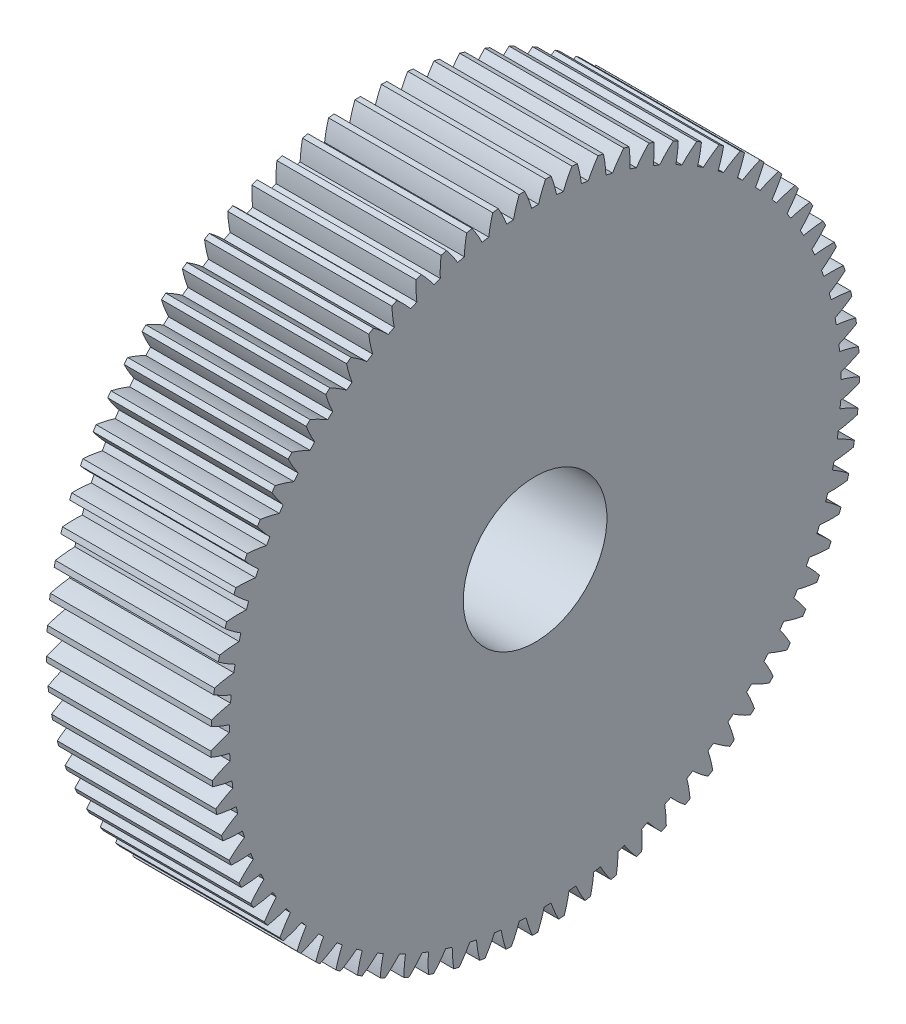
SolidWorks part; units mm, degrees
ref_plane "Plane1" through (0, 0, 0) normal (0, 0, 1) x (1, 0, 0)
ref_plane "Plane2" through (0, 0, 0) normal (0, 1, 0) x (1, 0, 0)
ref_plane "Plane3" through (0, 0, 0) normal (1, 0, 0) x (0, 0, -1)
other "Configuration Table"
sketch "HoldingSke" plane through (0, 0, 0) normal (0, 1, 0) x (1, 0, 0)
  line L0 (0, 0) -> (0.1125, -0.4872)
  line L1 (-15, 0) -> (100, 0) construction
  line L2 (0, 0) -> (-2.1039, 2.3779)
  line L3 (0, 0) -> (-11.863, 4.5341)
  line L4 (0, 0) -> (1.9427, 8.4147)
  line L5 (0, 0) -> (-46.8476, -17.4728)
  line L6 (0, 0) -> (-33.1585, -22.3721)
  line L7 (-2.1039, 2.3779) -> (8.6586, 51.2059)
  line L8 (-76.2, 54.61) -> (-72.9, 54.61)
  line L9 (-71.009, 38.7566) -> (-53.1078, 45.2721)
  line L10 (-76.2, 71.12) -> (104.1128, 71.12)
  line L11 (0, 0) -> (-40, 0)
  line L12 (-76.2, 101.6) -> (-76.133, 101.6)
  line L13 (24.9733, 27.94) -> (52.9518, 28.4284)
  line L14 (24.9733, 27.94) -> (24.9743, 27.94)
  line L15 (24.9733, 27.94) -> (100.4006, 29.5858)
  line L16 (-63.627, -2) -> (-12.827, -2)
  circle A0 centre (0, 0) radius 17.5
  circle A1 centre (0, 0) radius 37.5
  circle A2 centre (0, 0) radius 37.5
  circle A3 centre (0, 0) radius 17.5
  dimension "MHD" = 75
  dimension "Hub_dia" = 75
  dimension "Bore" = 35
  dimension "MBD" = 35
  dimension "Num_teeth" = 77
  dimension "Pitch" = 0.5
  dimension "Overall_len" = 50
  dimension "Show_teeth" = 77
  dimension "Thickness" = 40
  dimension "OAL" = 50.0001
  dimension "T_dim" = 3.3
  dimension "Ap" = 20
  dimension "H" = 19.05
  dimension "Pitch_radius" = 180.3128
  dimension "Width" = 40
  dimension "Backlash" = 0.067
  dimension "Addendum_fac" = 1
  dimension "Dedendum_fac" = 1.25
  dimension "Clearance_fac" = 0.25
  dimension "Dedendum_add" = 0.001
  dimension "Module" = 2
sketch "BasProSke" plane through (0, 0, 0) normal (0, 1, 0) x (1, 0, 0)
  line L0 (-10, 0) -> (60, 0) construction
  line L1 (0, 0) -> (0, 79)
  line L2 (0, 0) -> (40, 0)
  line L3 (40, 0) -> (40, 79)
  line L4 (40, 79) -> (0, 79)
  dimension "Thickness" = 40
  dimension "Diameter" = 158
revolve "Base-Revolve" add sketch "BasProSke" angle 360 about L0
sketch "TooCutSke" plane through (0, 0, 0) normal (1, 0, 0) x (0, 0, -1)
  line L1 (0, 0) -> (0, 107) construction
  line L2 (0, 0) -> (-1.6879, 76.9815) construction
  line L3 (0, 0) -> (-6.2803, 153.8444) construction
  line L4 (-1.6879, 76.9815) -> (-3.1402, 76.9222) construction
  arc A0 (0.8284, 74.4944) -> (-0.8284, 74.4944) centre (0, 0) ccw
  arc A1 (2.5605, 78.9839) -> (-2.5605, 78.9839) centre (0, 0) ccw
  circle A2 centre (0, 0) radius 77 construction
  circle A3 centre (0, 0) radius 72.3563 construction
  arc A4 (-0.8284, 74.4944) -> (-2.5605, 78.9839) centre (-30.3423, 65.687) ccw
  arc A5 (2.5605, 78.9839) -> (0.8284, 74.4944) centre (30.3423, 65.687) ccw
  dimension "Root_dia" = 148.998
  dimension "Overcut_dia" = 158.0508
  dimension "Pitch_dia" = 154
  dimension "Base_dia" = 144.7127
  dimension "Flank_rad" = 30.8
  dimension "Half_ang" = 2.338
  dimension "Half_CT" = 1.4534
extrude "ToothCut" cut sketch "TooCutSke" along normal through all
fillet "Breaks" [suppressed] radius 0.04
fillet "RootFillets" [suppressed] radius 0.501
pattern_circular "TeethCuts" count 77 every 4.675 about axis through (-10, 0, 0) along (1, 0, 0) of "ToothCut", "RootFillets", "Breaks"
sketch "HubNeaOneSke" plane through (0, 0, 0) normal (-1, 0, 0) x (0, 0, 1)
  circle A0 centre (0, 0) radius 37.5
  dimension "Diameter" = 75
extrude "HubNearOne" [suppressed] add sketch "HubNeaOneSke" along normal blind 10.0001
sketch "HubNeaBotSke" plane through (0, 0, 0) normal (-1, 0, 0) x (0, 0, 1)
  circle A0 centre (0, 0) radius 37.5
  dimension "Diameter" = 75
extrude "HubNearBoth" [suppressed] add sketch "HubNeaBotSke" along normal blind 5
ref_plane "FarPln" through (40, 0, 0) normal (1, 0, 0) x (0, 0, -1)
sketch "HubFarSke" plane through (40, 0, 0) normal (1, 0, 0) x (0, 0, -1)
  circle A0 centre (0, 0) radius 37.5
  dimension "Diameter" = 75
extrude "HubFar" [suppressed] add sketch "HubFarSke" along normal blind 5
sketch "BorSke" plane through (0, 0, 0) normal (1, 0, 0) x (0, 0, -1)
  circle A0 centre (0, 0) radius 17.5
  dimension "Diameter" = 35
extrude "Bore" cut sketch "BorSke" along normal mid plane 100.0001
sketch "KeySke" plane through (0, 0, 0) normal (1, 0, 0) x (0, 0, -1)
  line L0 (-5, 0) -> (-5, 20.8)
  line L1 (-5, 20.8) -> (5, 20.8)
  line L2 (5, 20.8) -> (5, 0)
  line L3 (0, 0) -> (0, 34) construction
  line L4 (-5, 0) -> (5, 0)
  dimension "Offset" = 20.8
  dimension "Width" = 10
extrude "Keyway" [suppressed] cut sketch "KeySke" along normal mid plane 100.0001
pattern_circular "Keyway2" [suppressed] count 2 every 90 about axis through (-10, 0, 0) along (1, 0, 0)
equation "' \"Module@HoldingSke\" = 6.35"
equation "' \"Num_teeth@HoldingSke\" = 12"
equation "' \"Ap@HoldingSke\" =  20"
equation "' \"Ap@HoldingSke\" = 20"
equation "' \"Width@HoldingSke\" = 0.5 * 25.4"
equation "' \"Hub_dia@HoldingSke\"= 1 * 25.4"
equation "' \"Hub_dia@HoldingSke\" = 1 * 25.4"
equation "' \"Overall_len@HoldingSke\" = 1.0 * 25.4"
equation "' \"Bore@HoldingSke\" = 0.75 * 25.4"
equation "' \"T_dim@HoldingSke\" = 0.1 * 25.4"
equation "' \"Width@KeySke\" = 0.25 * 25.4"
equation "' \"Show_teeth@HoldingSke\" = 13"
equation "' \"Backlash@HoldingSke\" = 0.009 * 25.4"
equation "' \"Addendum_fac@HoldingSke\" = 1.0"
equation "' \"Dedendum_fac@HoldingSke\" = 1.25"
equation "' \"Dedendum_add@HoldingSke\" = 0.00005 * 25.4"
equation "' \"Clearance_fac@HoldingSke\" = 0.25"
equation "\"Pitch@HoldingSke\" = 1 / \"Module@HoldingSke\""
equation "\"Overcut_dia@TooCutSke\" = (\"Num_teeth@HoldingSke\" + 2 * \"Addendum_fac@HoldingSke\") / \"Pitch@HoldingSke\" + 0.002 * 25.4"
equation "\"Pitch_dia@TooCutSke\" = \"Num_teeth@HoldingSke\" / \"Pitch@HoldingSke\""
equation "\"Base_dia@TooCutSke\" = \"Num_teeth@HoldingSke\" / \"Pitch@HoldingSke\" * cos((\"Ap@HoldingSke\"  * 3.14159265 / 180))"
equation "\"Root_dia@TooCutSke\" = (\"Num_teeth@HoldingSke\" + 2) / \"Pitch@HoldingSke\" - 2 * (\"Addendum_fac@HoldingSke\" + \"Dedendum_fac@HoldingSke\") / \"Pitch@HoldingSke\" - \"Dedendum_add@HoldingSke\" * 2"
equation "\"Half_ang@TooCutSke\" = 180 / \"Num_teeth@HoldingSke\""
equation "\"Half_CT@TooCutSke\" = \"Num_teeth@HoldingSke\" / \"Pitch@HoldingSke\" * sin((3.14159265 / 2 / \"Num_teeth@HoldingSke\")) / 2 - 7 * \"Backlash@HoldingSke\" / 4"
equation "\"Flank_rad@TooCutSke\" = \"Num_teeth@HoldingSke\" / \"Pitch@HoldingSke\" / 5"
equation "\"Radius@RootFillets\" = \"Clearance_fac@HoldingSke\" / \"Pitch@HoldingSke\" + \"Dedendum_add@HoldingSke\""
equation "\"Break_rad@Breaks\" = 0.02 / \"Pitch@HoldingSke\""
equation "\"Thickness@HoldingSke\" = \"Width@HoldingSke\""
equation "\"OAL@HoldingSke\" = \"Thickness@HoldingSke\""
equation "\"MHD@HoldingSke\" = (\"Num_teeth@HoldingSke\" + 2) / \"Pitch@HoldingSke\" - 2 * (\"Addendum_fac@HoldingSke\" + \"Dedendum_fac@HoldingSke\")  / \"Pitch@HoldingSke\" - \"Dedendum_add@HoldingSke\" * 2"
equation "\"MBD@HoldingSke\" = (\"Num_teeth@HoldingSke\" + 2) / \"Pitch@HoldingSke\" - 2 * (\"Addendum_fac@HoldingSke\" + \"Dedendum_fac@HoldingSke\")  / \"Pitch@HoldingSke\" - \"Dedendum_add@HoldingSke\" * 2 - 0.002 * 25.4"
equation "\"MHD@HoldingSke\" = ((sgn( \"MHD@HoldingSke\" - \"Hub_dia@HoldingSke\" )-1)*( \"MHD@HoldingSke\" - \"Hub_dia@HoldingSke\" ))/-2+ \"Hub_dia@HoldingSke\""
equation "\"MBD@HoldingSke\" = ((sgn( \"MBD@HoldingSke\" - \"Bore@HoldingSke\" )-1)*( \"MBD@HoldingSke\" - \"Bore@HoldingSke\" ))/-2+ \"Bore@HoldingSke\""
equation "\"OAL@HoldingSke\" = ((sgn( \"OAL@HoldingSke\" - \"Overall_len@HoldingSke\" )+1)*( \"OAL@HoldingSke\" - \"Overall_len@HoldingSke\" ))/2 + \"Overall_len@HoldingSke\" + 0.000002 * 25.4"
equation "\"Num_teeth@TeethCuts\" = int( \"Show_teeth@HoldingSke\" ) + 1"
equation "\"Num_teeth@TeethCuts\" = ((sgn( \"Num_teeth@TeethCuts\" - \"Num_teeth@HoldingSke\" )-1)*( \"Num_teeth@TeethCuts\" - \"Num_teeth@HoldingSke\" ))/-2+ \"Num_teeth@HoldingSke\""
equation "\"Num_teeth@TeethCuts\" = ((sgn( \"Num_teeth@TeethCuts\" - 2.0)+1)*( \"Num_teeth@TeethCuts\" - 2.0))/2 +2.0"
equation "\"Angle@TeethCuts\" = 360.0 / \"Num_teeth@HoldingSke\""
equation "\"Diameter@BasProSke\" = (\"Num_teeth@HoldingSke\" + 2 * \"Addendum_fac@HoldingSke\") / \"Pitch@HoldingSke\""
equation "\"Thickness@BasProSke\"  = \"Thickness@HoldingSke\""
equation "' \"Fillet_rad@BasProSke\" =  \"Thickness@HoldingSke\" * 0.05"
equation "' \"Fillet_rad@BasProSke\" = \"Thickness@HoldingSke\" * 0.05"
equation "\"MHD@HoldingSke\" = ((sgn( \"MHD@HoldingSke\" - \"Root_dia@TooCutSke\" )-1)*( \"MHD@HoldingSke\" - \"Root_dia@TooCutSke\" ))/-2+ \"Root_dia@TooCutSke\""
equation "\"Diameter@HubNeaOneSke\" = \"MHD@HoldingSke\""
equation "\"Length@HubNearOne\" = \"OAL@HoldingSke\" - \"Thickness@BasProSke\""
equation "\"Diameter@HubNeaBotSke\" = \"MHD@HoldingSke\""
equation "\"Length@HubNearBoth\" = ( \"OAL@HoldingSke\" - \"Thickness@BasProSke\" ) / 2.0"
equation "\"Thickness@FarPln\" = \"Thickness@BasProSke\""
equation "\"Diameter@HubFarSke\" = \"MHD@HoldingSke\""
equation "\"Length@HubFar\" = ( \"OAL@HoldingSke\" - \"Thickness@BasProSke\" ) / 2.0"
equation "\"Diameter@BorSke\" = \"MBD@HoldingSke\""
equation "\"D1@Bore\" = \"OAL@HoldingSke\" * 2.0"
equation "\"D1@Keyway\" = \"OAL@HoldingSke\" * 2.0"
equation "\"Offset@KeySke\" = \"T_dim@HoldingSke\" + \"MBD@HoldingSke\" / 2.0"
